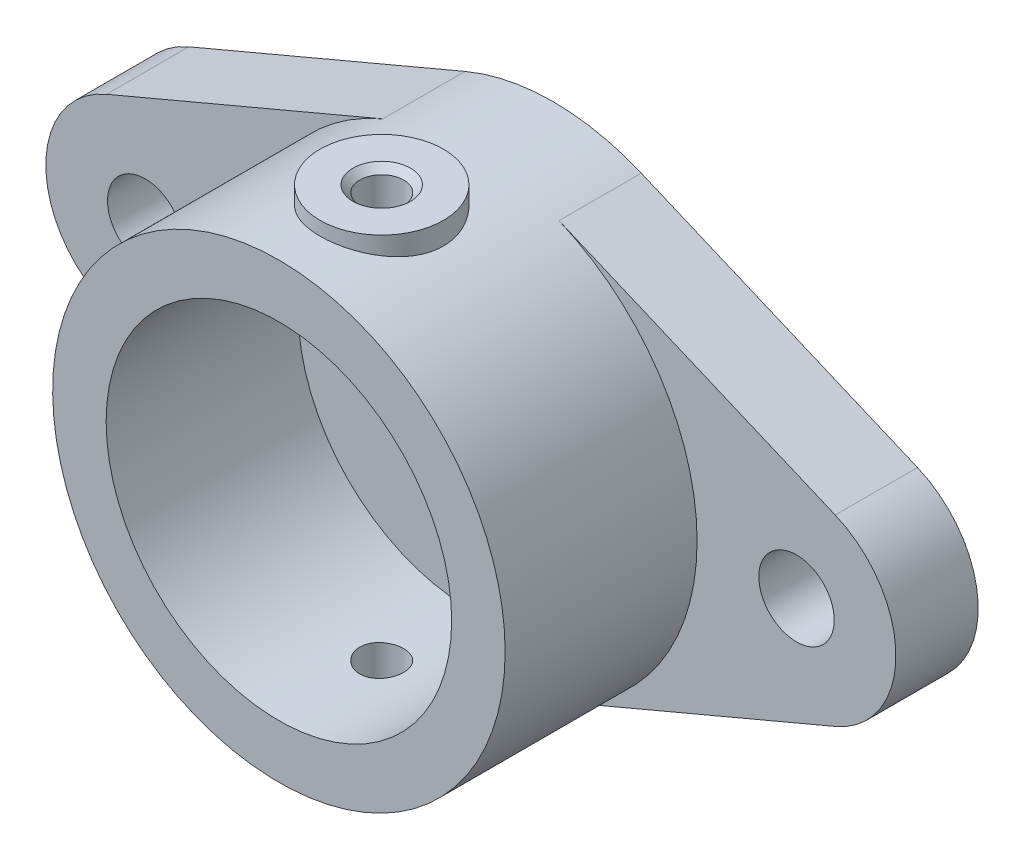
SolidWorks part; units mm, degrees
ref_plane "Front Plane" through (0, 0, 0) normal (0, 0, 1) x (1, 0, 0)
ref_plane "Top Plane" through (0, 0, 0) normal (0, 1, 0) x (1, 0, 0)
ref_plane "Right Plane" through (0, 0, 0) normal (1, 0, 0) x (0, 0, -1)
sketch "Sketch1" plane through (0, 0, 0) normal (0, 0, 1) x (1, 0, 0)
  circle A0 centre (0, 0) radius 12.6
  circle A1 centre (0, 0) radius 16.5
  dimension "D1" = 25.2
  dimension "D2" = 33
extrude "Boss-Extrude1" add sketch "Sketch1" along normal blind 15
sketch "Sketch2" plane through (0, 0, 0) normal (0, 0, -1) x (-1, 0, 0)
  circle A0 centre (0, 0) radius 16.5
  circle A1 centre (0, 0) radius 16.5 construction
extrude "Boss-Extrude2" add sketch "Sketch2" along normal blind 5
ref_plane "Plane1" through (0, 17.5, 0) normal (0, 1, 0) x (1, 0, 0)
sketch "Sketch3" plane through (0, 17.5, 0) normal (0, 1, 0) x (1, 0, 0)
  line L0 (-16.5, -15) -> (16.5, -15) construction
  circle A0 centre (0, -7.5) radius 4.5
  dimension "D1" = 9
  dimension "D2" = 7.5
extrude "Boss-Extrude3" add sketch "Sketch3" against normal up to surface (1 mm away)
sketch "Sketch4" plane through (0, 17.5, 0) normal (0, 1, 0) x (1, 0, 0)
  line L0 (-16.5, -15) -> (16.5, -15) construction
  circle A0 centre (0, -7.5) radius 1.6
  dimension "D1" = 3.2
  dimension "D2" = 7.5
extrude "Cut-Extrude1" cut sketch "Sketch4" against normal up to surface (4.9 mm away)
pattern_circular "CirPattern1" count 2 over 360 about axis through (0, 0, 15) along (0, 0, 1) of "Cut-Extrude1", "Boss-Extrude3"
chamfer "Chamfer1" distance 0.5 angle 45 2 edges at (0, -17.5, 9.1) (0, 17.5, 9.1)
sketch "Sketch5" plane through (0, 0, -5) normal (0, 0, -1) x (-1, 0, 0)
  line L0 (26.5737, 6.6775) -> (6.4263, 15.1971)
  line L1 (26.5737, -6.6775) -> (6.4263, -15.1971)
  line L2 (-6.4263, 15.1971) -> (-26.5737, 6.6775)
  line L3 (-6.4263, -15.1971) -> (-26.5737, -6.6775)
  circle A0 centre (23.75, 0) radius 2.75
  circle A1 centre (-23.75, 0) radius 2.75
  arc A2 (26.5737, -6.6775) -> (26.5737, 6.6775) centre (23.75, 0) ccw
  arc A3 (-26.5737, 6.6775) -> (-26.5737, -6.6775) centre (-23.75, 0) ccw
  circle A4 centre (0, 0) radius 16.5 construction
  circle A6 centre (0, 0) radius 16.5 construction
  circle A8 centre (0, 0) radius 16.5 construction
  arc A9 (6.4263, 15.1971) -> (-6.4263, 15.1971) centre (0, 0) ccw
  arc A10 (6.4263, -15.1971) -> (-6.4263, -15.1971) centre (0, 0) cw
  dimension "D3" = 5.5
  dimension "D1" = 23.75
  dimension "D2" = 23.75
extrude "Boss-Extrude4" add sketch "Sketch5" against normal blind 6
sketch "Sketch6" plane through (0, 0, 1) normal (0, 0, 1) x (1, 0, 0)
  circle A0 centre (-23.75, 0) radius 4.5
  circle A1 centre (23.75, 0) radius 4.5
  dimension "D1" = 9
extrude "Cut-Extrude2" [suppressed] cut sketch "Sketch6" against normal blind 5
